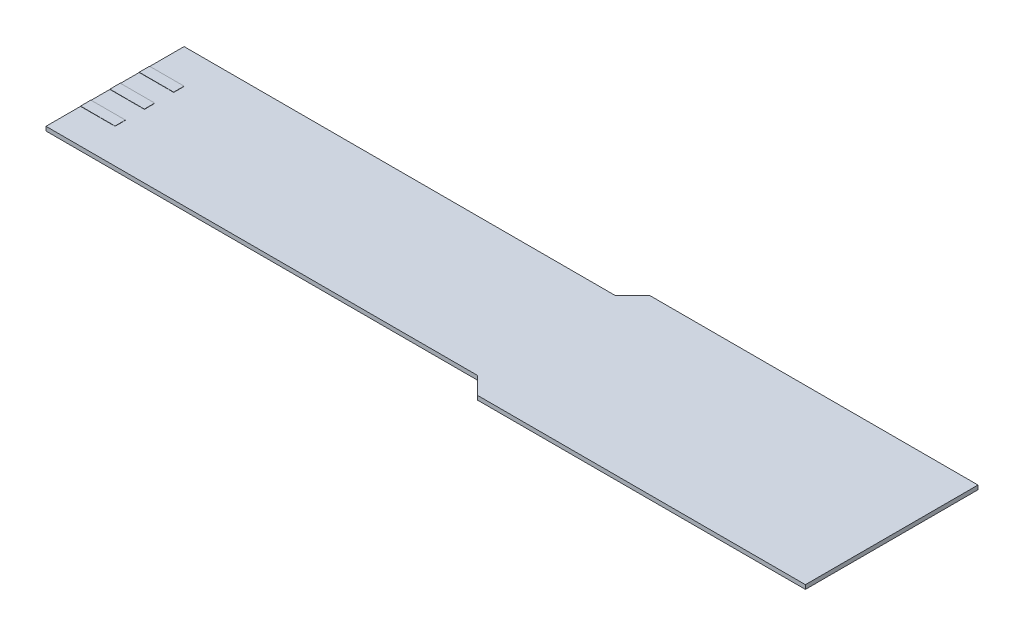
SolidWorks part; units mm, degrees
ref_plane "Front Plane" through (0, 0, 0) normal (0, 0, 1) x (1, 0, 0)
ref_plane "Top Plane" through (0, 0, 0) normal (0, 1, 0) x (1, 0, 0)
ref_plane "Right Plane" through (0, 0, 0) normal (1, 0, 0) x (0, 0, -1)
sketch "Sketch1" plane through (0, 0, 0) normal (0, 1, 0) x (1, 0, 0)
  line L0 (0, 0) -> (0, -10) construction
  line L1 (62.5, 10) -> (65, 12.5)
  line L2 (0, -10) -> (62.5, -10)
  line L3 (0, -10) -> (0, 10)
  line L4 (0, 10) -> (62.5, 10)
  line L5 (62.5, -10) -> (62.5, 10)
  line L6 (62.5, -10) -> (65, -12.5)
  line L7 (65, 12.5) -> (112.5, 12.5)
  line L8 (65, 12.5) -> (65, -12.5)
  line L9 (65, -12.5) -> (112.5, -12.5)
  line L10 (112.5, 12.5) -> (112.5, -12.5)
  dimension "D1" = 10
  dimension "D2" = 20
  dimension "D3" = 62.5
  dimension "D4" = 2.5
  dimension "D5" = 2.5
  dimension "D6" = 47.5
  dimension "D7" = 25
extrude "Boss-Extrude1" add sketch "Sketch1" along normal blind 0.6 from offset 0.6 contours L2 L5 L4 L3 | L8 L1 L5 L6 | L10 L7 L8 L9 offset against normal yes
sketch "Sketch2" plane through (0, 0, 0) normal (0, 1, 0) x (1, 0, 0)
  line L0 (0, -10) -> (0, 10) construction
  line L1 (0, -0.75) -> (5, -0.75)
  line L2 (0, -0.75) -> (0, 0.75)
  line L3 (0, 0.75) -> (5, 0.75)
  line L4 (5, -0.75) -> (5, 0.75)
  line L5 (0, 3.5) -> (0, 5)
  line L6 (0, 3.5) -> (5, 3.5)
  line L7 (5, 3.5) -> (5, 5)
  line L8 (0, 5) -> (5, 5)
  line L9 (0, -5) -> (0, -3.5)
  line L10 (0, -5) -> (5, -5)
  line L11 (5, -5) -> (5, -3.5)
  line L12 (0, -3.5) -> (5, -3.5)
  dimension "D1" = 1.5
  dimension "D2" = 0.75
  dimension "D3" = 5
  dimension "D5" = 2.75
  dimension "D7" = 2.75
  dimension "D4" = 2
  dimension "D6" = 2
extrude "Boss-Extrude2" add sketch "Sketch2" against normal blind 0.3 from offset 0.035 separate body
